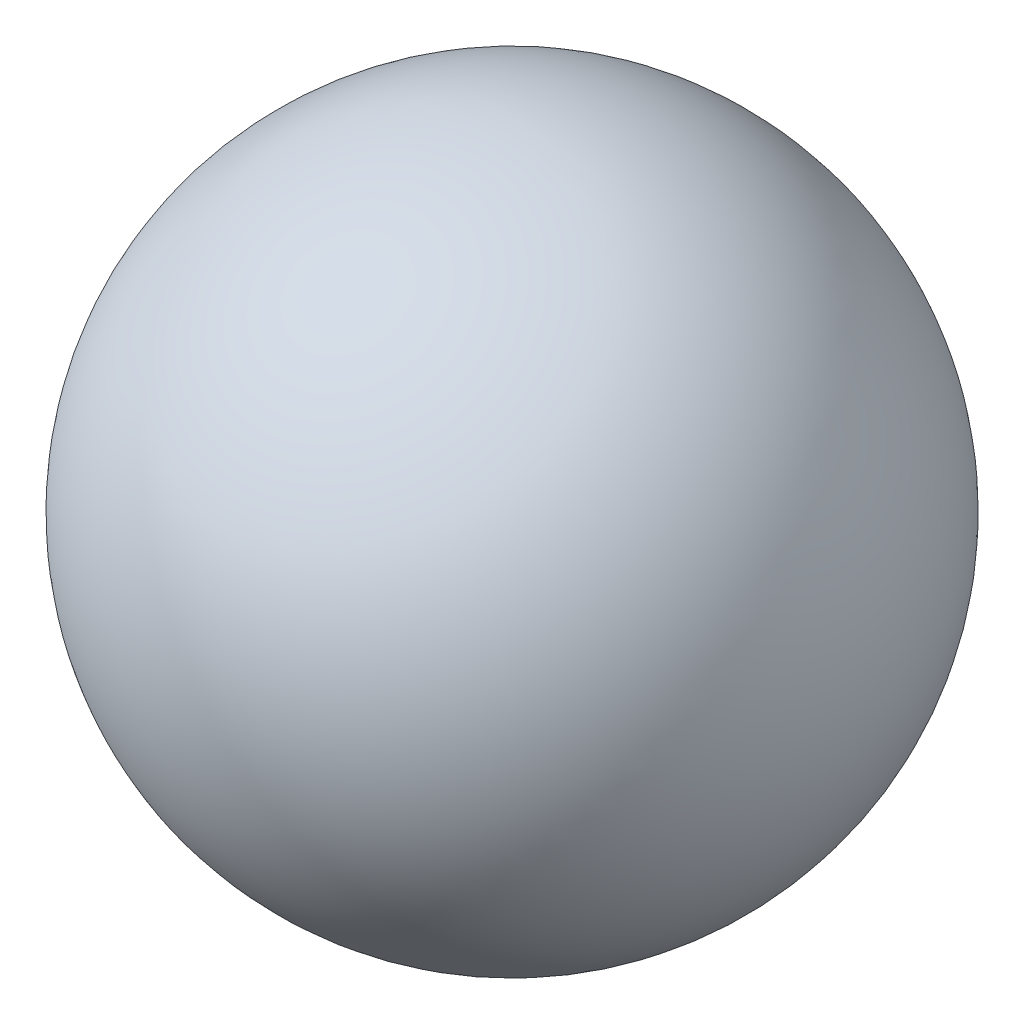
SolidWorks part; units mm, degrees
material "Water"
ref_plane "Front Plane" through (0, 0, 0) normal (0, 0, 1) x (1, 0, 0)
ref_plane "Top Plane" through (0, 0, 0) normal (0, 1, 0) x (1, 0, 0)
ref_plane "Right Plane" through (0, 0, 0) normal (1, 0, 0) x (0, 0, -1)
sketch "Sketch1" plane through (0, 0, 0) normal (0, 1, 0) x (1, 0, 0)
  line L0 (0, 0) -> (0, 26.3371) construction
  line L1 (0, -12.7) -> (0, 12.7)
  arc A0 (0, 12.7) -> (0, -12.7) centre (0, 0) ccw
  dimension "D1" = 25.4
revolve "Revolve4" add sketch "Sketch1" angle 360 about L0
